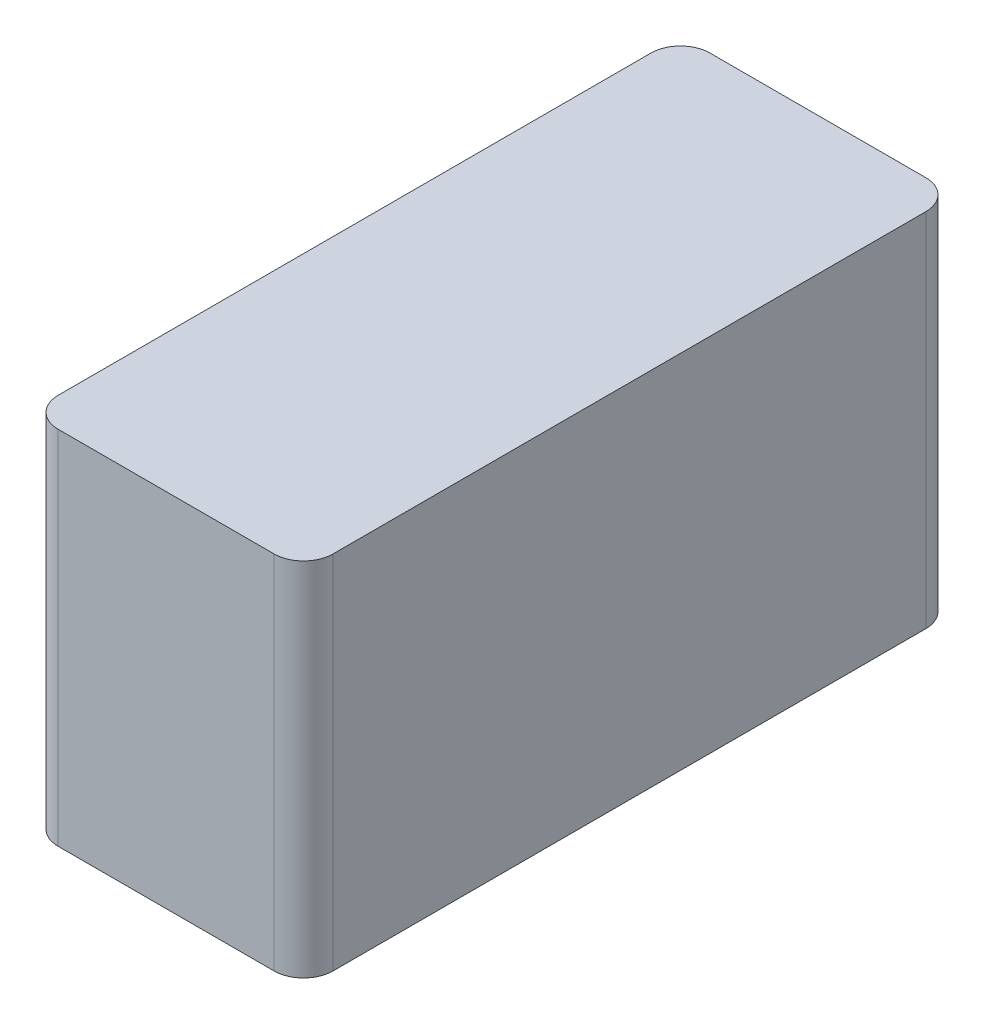
SolidWorks part; units mm, degrees
ref_plane "前视基准面" through (0, 0, 0) normal (0, 0, 1) x (1, 0, 0)
ref_plane "上视基准面" through (0, 0, 0) normal (0, 1, 0) x (1, 0, 0)
ref_plane "右视基准面" through (0, 0, 0) normal (1, 0, 0) x (0, 0, -1)
sketch "草图1" plane through (0, 0, 0) normal (1, 0, 0) x (0, 0, -1)
  line L1 (0, 0) -> (332, 0)
  line L2 (0, 0) -> (0, -184)
  line L3 (0, -184) -> (332, -184)
  line L4 (332, 0) -> (332, -184)
extrude "凸台-拉伸1" add sketch "草图1" along normal blind 140
fillet "圆角1" radius 15 4 edges at (0, -92, -332) (140, -92, -332) (140, -92, 0) (0, -92, 0)
